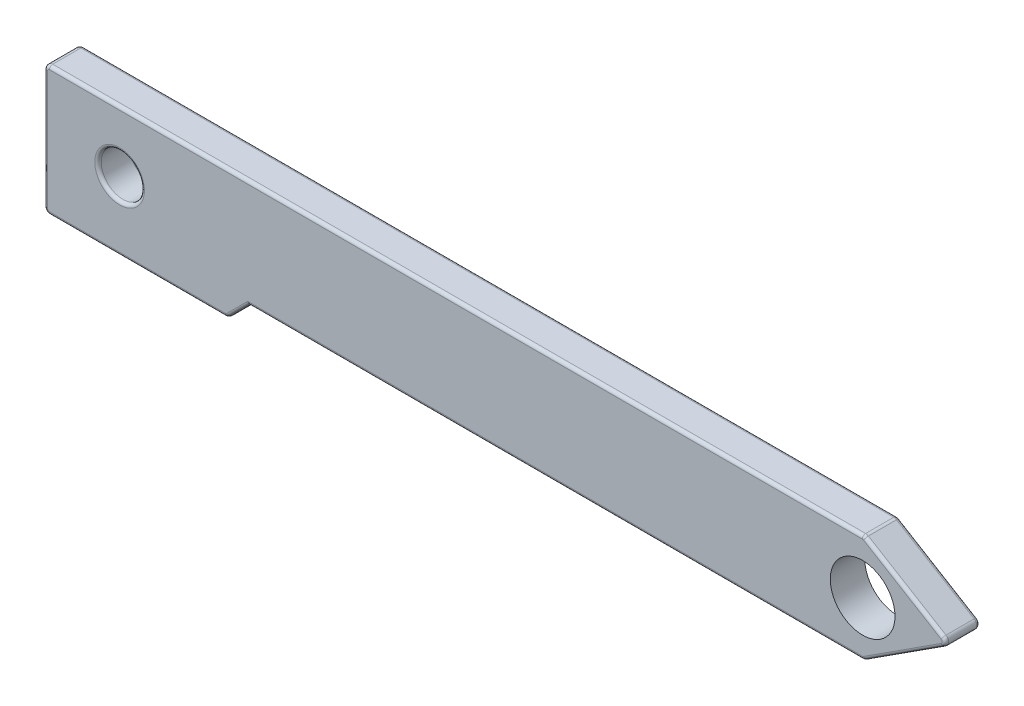
SolidWorks part; units mm, degrees
ref_plane "Płaszczyzna przednia" through (0, 0, 0) normal (0, 0, 1) x (1, 0, 0)
ref_plane "Płaszczyzna górna" through (0, 0, 0) normal (0, 1, 0) x (1, 0, 0)
ref_plane "Płaszczyzna prawa" through (0, 0, 0) normal (1, 0, 0) x (0, 0, -1)
sketch "Sketch1" plane through (0, 0, 0) normal (0, 0, 1) x (1, 0, 0)
  line L0 (20.7118, 0) -> (-7.7146, 0)
  line L1 (-7.7146, 0) -> (-8.6413, -0.9268)
  line L2 (-8.8181, -1) -> (-16.9646, -1)
  line L3 (-17.2146, -0.75) -> (-17.2146, 4.75)
  line L4 (-16.9646, 5) -> (20.7157, 5)
  line L5 (20.8451, 4.9639) -> (24.4431, 2.7866)
  line L6 (24.4492, 2.3626) -> (20.8473, 0.0399)
  circle A0 centre (-13.7146, 2.2) radius 1
  arc A1 (20.7157, 5) -> (20.8451, 4.9639) centre (20.7157, 4.75) cw
  arc A2 (24.4431, 2.7866) -> (24.4492, 2.3626) centre (24.3137, 2.5727) cw
  arc A3 (20.7118, 0) -> (20.8473, 0.0399) centre (20.7118, 0.25) ccw
  arc A4 (-8.6413, -0.9268) -> (-8.8181, -1) centre (-8.8181, -0.75) cw
  arc A5 (-16.9646, -1) -> (-17.2146, -0.75) centre (-16.9646, -0.75) cw
  arc A6 (-17.2146, 4.75) -> (-16.9646, 5) centre (-16.9646, 4.75) cw
  point P10 (20.7854, 5)
  point P15 (24.7854, 2.5794)
  point P18 (20.7854, 0)
  point P21 (-8.7146, -1)
  point P24 (-17.2146, -1)
  point P27 (-17.2146, 5)
  dimension "D7" = 2
  dimension "D11" = 0.25
  dimension "D1" = 4
  dimension "D2" = 42
  dimension "D3" = 8.5
  dimension "D4" = 5
  dimension "D5" = 6
  dimension "D6" = 4
  dimension "D8" = 3.5
  dimension "D9" = 3.2
  dimension "D10" = 135
extrude "Boss-Extrude1" add sketch "Sketch1" along normal blind 1.6
fillet "Fillet1" radius 0.15 26 edges at (6.4986, 0, 0) (20.7825, 0.0102, 0) (22.6483, 1.2012, 0) (24.5637, 2.5763, 0) (22.6441, 3.8752, 0) (20.7829, 4.9908, 0) (-8.1779, -0.4634, 0) (-8.7224, -0.981, 0) (-12.8913, -1, 0) (-17.1413, -0.9268, 0) (-17.2146, 2, 0) (-17.1413, 4.9268, 0) (6.4986, 0, 1.6) (20.7825, 0.0102, 1.6) (22.6483, 1.2012, 1.6) (24.5637, 2.5763, 1.6) (22.6441, 3.8752, 1.6) (20.7829, 4.9908, 1.6) (-8.1779, -0.4634, 1.6) (-8.7224, -0.981, 1.6) (-12.8913, -1, 1.6) (-17.1413, -0.9268, 1.6) (-17.2146, 2, 1.6) (-17.1413, 4.9268, 1.6) (1.8756, 5, 0) (1.8756, 5, 1.6)
sketch "Sketch2" plane through (0, 0, 1.6) normal (0, 0, 1) x (1, 0, 0)
  line L1 (-16.9646, 5) -> (20.7157, 5) construction
  circle A0 centre (20.7274, 2.5) radius 1.5
  point P2 (0, 0)
  point P5 (0, 0)
  dimension "D1" = 3
  dimension "D2" = 2.5
extrude "Cut-Extrude1" cut sketch "Sketch2" against normal through all
fillet "Fillet2" radius 0.15 2 edges at (-12.7146, 2.2, 0) (-12.7146, 2.2, 1.6)
sketch "Sketch3" plane through (0, 0, 0) normal (0, 0, -1) x (-1, 0, 0)
  line L0 (-10.7675, 4.35) -> (1.2325, 4.35)
  line L1 (16.9646, 4.85) -> (-20.7157, 4.85) construction
  arc A0 (-10.7675, 4.35) -> (1.2325, 4.35) centre (-4.7675, 23.4288) ccw
  dimension "D4" = 20
  dimension "D1" = 10
  dimension "D2" = 0.5
  dimension "D3" = 12
extrude "Cut-Extrude2" cut sketch "Sketch3" against normal blind 0.5
fillet "Fillet3" radius 0.1 2 edges at (-1.2325, 4.35, 0.25) (10.7675, 4.35, 0.25)
fillet "Fillet4" radius 0.15 4 edges at (-0.6405, 4.2635, 0) (4.7675, 3.4288, 0) (10.1754, 4.2635, 0) (4.7675, 4.35, 0)
